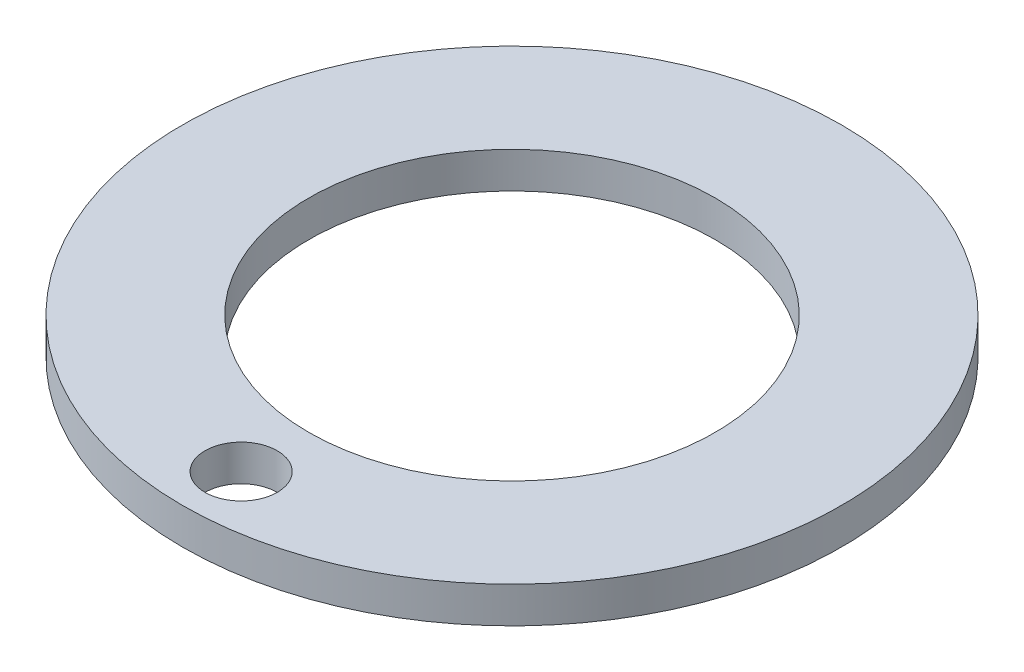
SolidWorks part; units mm, degrees
ref_plane "Front Plane" through (0, 0, 0) normal (0, 0, 1) x (1, 0, 0)
ref_plane "Top Plane" through (0, 0, 0) normal (0, 1, 0) x (1, 0, 0)
ref_plane "Right Plane" through (0, 0, 0) normal (1, 0, 0) x (0, 0, -1)
sketch "Sketch1" plane through (0, 0, 0) normal (0, 1, 0) x (1, 0, 0)
  circle A0 centre (0, -0.085) radius 11.25
  circle A1 centre (0, -0.085) radius 18.25
  circle A2 centre (0, -15.085) radius 2
  point P6 (0, 0)
  point P7 (0, 0)
  dimension "D1" = 22.5
  dimension "D2" = 36.5
  dimension "D3" = 4
  dimension "D4" = 15
extrude "Boss-Extrude1" add sketch "Sketch1" along normal blind 2
